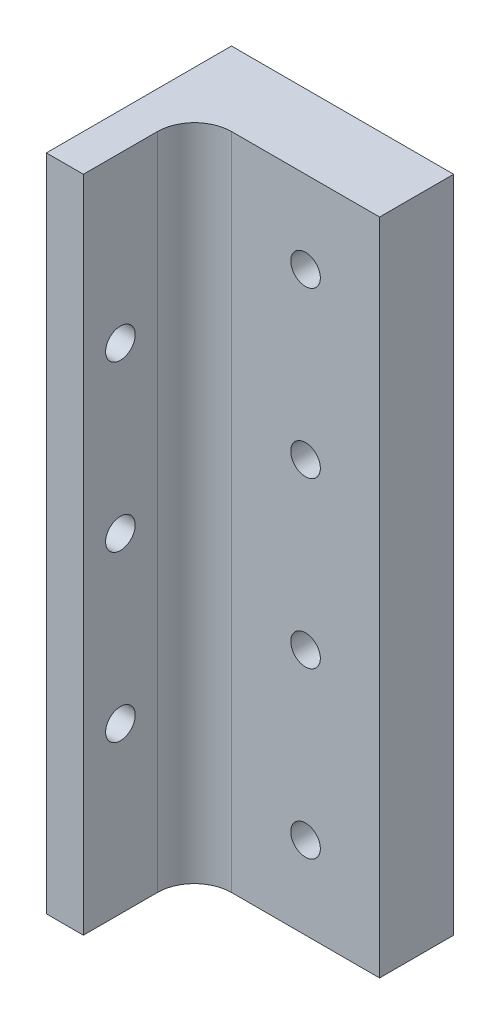
SolidWorks part; units mm, degrees
ref_plane "Front Plane" through (0, 0, 0) normal (0, 0, 1) x (1, 0, 0)
ref_plane "Top Plane" through (0, 0, 0) normal (0, 1, 0) x (1, 0, 0)
ref_plane "Right Plane" through (0, 0, 0) normal (1, 0, 0) x (0, 0, -1)
sketch "Sketch1" plane through (0, 0, 0) normal (0, 0, 1) x (1, 0, 0)
  line L1 (50, -25) -> (-50, -25)
  line L2 (50, -25) -> (50, 25)
  line L3 (50, 25) -> (-50, 25)
  line L4 (-50, -25) -> (-50, 25)
  line L5 (50, -25) -> (-50, 25) construction
  line L6 (50, 25) -> (-50, -25) construction
  arc A0 (-45, 25) -> (45, 25) centre (0, 76.0588) ccw
  arc A1 (-45.0185, -25) -> (45.0185, -25) centre (0, -76.1077) cw
  point P0 (0, 0)
  point P6 (-45, 25)
  point P7 (-45.0185, -25)
  point P8 (45, 25)
  point P9 (45.0185, -25)
  point P16 (0, -8)
  point P17 (0, 8)
  dimension "D1" = 50
  dimension "D2" = 100
  dimension "D3" = 5
  dimension "D4" = 5
  dimension "D5" = 8
  dimension "D6" = 8
extrude "Boss-Extrude1" add sketch "Sketch1" along normal blind 10 contours L1 A1 L2 L3 A0 L4
sketch "Sketch2" plane through (0, 25, 0) normal (0, 1, 0) x (1, 0, 0)
  line L0 (-50, -5) -> (50, -5) construction
  line L1 (-50, -10) -> (-50, 0) construction
  line L2 (50, -10) -> (50, 0) construction
  line L3 (-45, -10) -> (-45, 0) construction
  circle A0 centre (-48, -5) radius 1.5
  circle A1 centre (48, -5) radius 1.5
  point P7 (-48, -5)
  point P11 (48, -5)
  dimension "D2" = 96
  dimension "D3" = 3
extrude "Cut-Extrude1" cut sketch "Sketch2" against normal through all both and the other way through all
sketch "Sketch9" plane through (50, 0, 0) normal (1, 0, 0) x (0, 0, -1)
  line L1 (0, 25) -> (-10, 25)
  line L2 (0, 25) -> (0, -25)
  line L3 (0, -25) -> (-10, -25)
  line L4 (-10, 25) -> (-10, -25)
extrude "Boss-Extrude9" add sketch "Sketch9" along normal blind 5
sketch "Sketch10" plane through (-50, 0, 0) normal (-1, 0, 0) x (0, 0, 1)
  line L1 (10, -25) -> (0, -25)
  line L2 (10, -25) -> (10, 25)
  line L3 (10, 25) -> (0, 25)
  line L4 (0, -25) -> (0, 25)
extrude "Boss-Extrude10" add sketch "Sketch10" along normal blind 5
sketch "Sketch11" plane through (0, 25, 0) normal (0, 1, 0) x (1, 0, 0)
  line L0 (50, 0) -> (50, -7)
  line L1 (55, 0) -> (45, 0) construction
  line L2 (-50, 0) -> (-50, -7)
  line L3 (-45, 0) -> (-55, 0) construction
  line L4 (50, -7) -> (45, -7)
  line L5 (45, -10) -> (45, 0) construction
  line L6 (-50, -7) -> (-45, -7)
  line L7 (-45, -10) -> (-45, 0) construction
  line L8 (50, 0) -> (55, 0)
  line L9 (55, 0) -> (55, -10)
  line L10 (55, -10) -> (45, -10)
  line L11 (45, -10) -> (45, -7)
  line L12 (-45, -7) -> (-45, -10)
  line L13 (-45, -10) -> (-55, -10)
  line L14 (-55, -10) -> (-55, 0)
  line L15 (-55, 0) -> (-50, 0)
  circle A1 centre (48, -5) radius 1.5 construction
  circle A2 centre (-48, -5) radius 1.5 construction
  dimension "D1" = 100
  dimension "D2" = 2
  dimension "D3" = 2
extrude "Boss-Extrude11" add sketch "Sketch11" along normal blind 2
sketch "Sketch12" plane through (0, 27, 0) normal (0, 1, 0) x (1, 0, 0)
  line L0 (45, -7) -> (45, -10) construction
  line L1 (55, -10) -> (45, -10)
  line L2 (55, -10) -> (55, 0)
  line L3 (55, 0) -> (45, 0)
  line L4 (45, -10) -> (45, 0)
  line L6 (-55, -10) -> (-45, -10)
  line L7 (-55, -10) -> (-55, 0)
  line L8 (-55, 0) -> (-45, 0)
  line L9 (-45, -10) -> (-45, 0)
  dimension "D1" = 0
extrude "Boss-Extrude12" add sketch "Sketch12" along normal blind 5
sketch "Sketch13" plane through (0, 25, 0) normal (0, 1, 0) x (1, 0, 0)
  circle A0 centre (48, -5) radius 1.5
  circle A1 centre (-48, -5) radius 1.5
extrude "Cut-Extrude2" cut sketch "Sketch13" along normal up to surface (7 mm away) up to face at (-50, 32, 5)
sketch "Sketch14" plane through (0, -25, 0) normal (0, -1, 0) x (1, 0, 0)
  line L0 (50.0092, 0) -> (50.0092, 7)
  line L1 (55, 0) -> (45.0185, 0) construction
  line L2 (50.0092, 7) -> (45.0185, 7)
  line L3 (45.0185, 10) -> (45.0185, 0) construction
  line L4 (-50.0092, 0) -> (-50.0092, 7)
  line L5 (-45.0185, 0) -> (-55, 0) construction
  line L6 (-50.0092, 7) -> (-45.0185, 7)
  line L7 (-45.0185, 10) -> (-45.0185, 0) construction
  line L8 (-45.0185, 7) -> (-45.0185, 10)
  line L9 (-45.0185, 10) -> (-55, 10)
  line L10 (-55, 10) -> (-55, 0)
  line L11 (-55, 0) -> (-50.0092, 0)
  line L12 (45.0185, 7) -> (45.0185, 10)
  line L13 (45.0185, 10) -> (55, 10)
  line L14 (55, 10) -> (55, 0)
  line L15 (55, 0) -> (50.0092, 0)
  circle A0 centre (48, 5) radius 1.5 construction
  dimension "D1" = 2
extrude "Boss-Extrude13" add sketch "Sketch14" along normal blind 2
sketch "Sketch15" plane through (0, -27, 0) normal (0, -1, 0) x (1, 0, 0)
  line L1 (-55, 0) -> (-45.0185, 0)
  line L2 (-55, 0) -> (-55, 10)
  line L3 (-55, 10) -> (-45.0185, 10)
  line L4 (-45.0185, 0) -> (-45.0185, 10)
  line L5 (55, 10) -> (45.0185, 10)
  line L6 (55, 10) -> (55, 0)
  line L7 (55, 0) -> (45.0185, 0)
  line L8 (45.0185, 10) -> (45.0185, 0)
extrude "Boss-Extrude14" add sketch "Sketch15" along normal blind 30
sketch "Sketch16" plane through (0, -25, 0) normal (0, -1, 0) x (1, 0, 0)
  circle A1 centre (48, 5) radius 1.5
  circle A3 centre (-48, 5) radius 1.5
extrude "Cut-Extrude3" cut sketch "Sketch16" along normal up to surface (32 mm away) up to face at (-50.0092, -57, 5)
sketch "Sketch17" plane through (-55, 0, 0) normal (-1, 0, 0) x (0, 0, 1)
  line L1 (0, 32) -> (10, 32)
  line L2 (0, 32) -> (0, -57)
  line L3 (0, -57) -> (10, -57)
  line L4 (10, 32) -> (10, -57)
extrude "Boss-Extrude15" add sketch "Sketch17" along normal blind 30
sketch "Sketch19" plane through (0, 0, 10) normal (0, 0, 1) x (1, 0, 0)
  line L0 (-45.0185, -57) -> (-85, -57) construction
  line L1 (-85, 32) -> (-80, 32)
  line L2 (-85, 32) -> (-85, -57)
  line L3 (-85, -57) -> (-80, -57)
  line L4 (-80, 32) -> (-80, -57)
  dimension "D1" = 5
extrude "Boss-Extrude16" add sketch "Sketch19" along normal blind 15
fillet "Fillet1" radius 5 1 edges at (-80, -12.5, 10)
sketch "Sketch20" plane through (-80, 0, 0) normal (1, 0, 0) x (0, 0, -1)
  line L0 (-15, 32) -> (-25, 32) construction
  circle A0 centre (-20, 9.75) radius 2
  circle A1 centre (-20, -12.5) radius 2
  circle A2 centre (-20, -34.75) radius 2
  point P9 (-20, 9.75)
  point P10 (-20, -12.5)
  point P11 (-20, -34.75)
extrude "Cut-Extrude4" cut sketch "Sketch20" against normal through all
sketch "Sketch21" plane through (0, 0, 10) normal (0, 0, 1) x (1, 0, 0)
  line L0 (-65, -34.75) -> (-65, -57) construction
  line L4 (-45.0185, -57) -> (-75, -57) construction
  line L6 (-65, 32) -> (-65, 9.75) construction
  line L7 (-75, 32) -> (-45, 32) construction
  line L8 (-65, 9.75) -> (-65, -12.5) construction
  line L9 (-65, -12.5) -> (-65, -34.75) construction
  circle A0 centre (-65, 20.875) radius 2
  circle A1 centre (-65, -1.375) radius 2
  circle A2 centre (-65, -23.625) radius 2
  circle A3 centre (-65, -45.875) radius 2
  point P1 (-65, -34.75)
  point P7 (-65, 9.75)
  point P8 (-65, -12.5)
  point P11 (-65, 20.875)
  point P13 (-65, -1.375)
  point P14 (-65, -23.625)
  point P15 (-65, -45.875)
extrude "Cut-Extrude5" cut sketch "Sketch21" against normal blind 10
sketch "Sketch22" plane through (0, 0, 10) normal (0, 0, 1) x (1, 0, 0)
  line L0 (-75, 32) -> (-45, 32) construction
  line L1 (55, -57) -> (-55, -57)
  line L2 (55, -57) -> (55, 32)
  line L3 (55, 32) -> (-55, 32)
  line L4 (-55, -57) -> (-55, 32)
  line L5 (-75, 32) -> (-75, -57) construction
  dimension "D1" = 20
extrude "Cut-Extrude6" cut sketch "Sketch22" against normal through all
